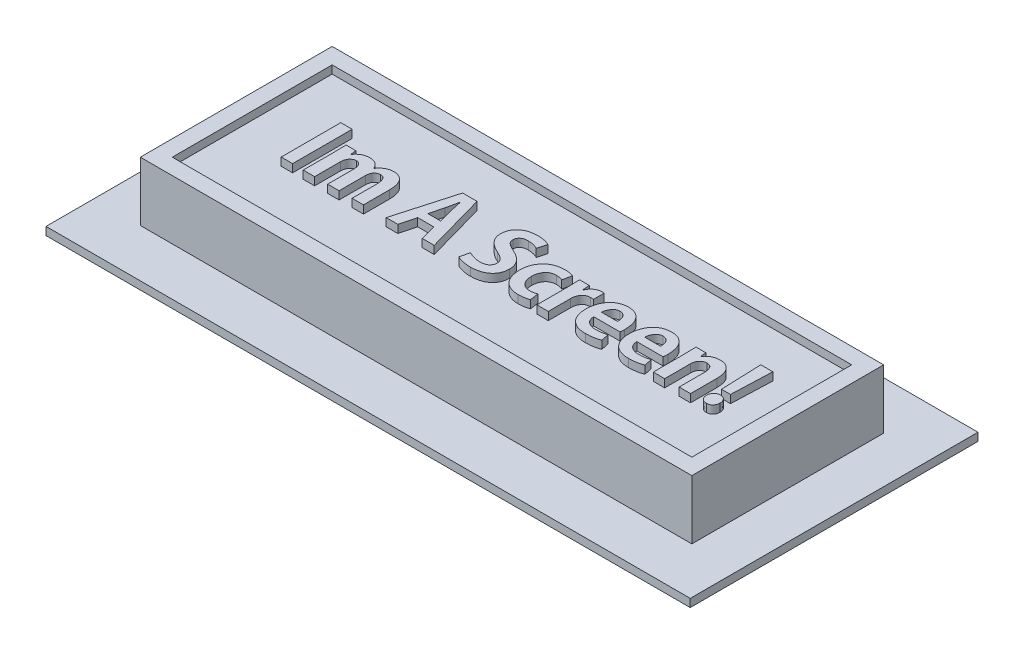
SolidWorks part; units mm, degrees
ref_plane "Front Plane" through (0, 0, 0) normal (0, 0, 1) x (1, 0, 0)
ref_plane "Top Plane" through (0, 0, 0) normal (0, 1, 0) x (1, 0, 0)
ref_plane "Right Plane" through (0, 0, 0) normal (1, 0, 0) x (0, 0, -1)
sketch "Sketch1" plane through (0, 0, 0) normal (0, 1, 0) x (1, 0, 0)
  line L1 (40.3, -18) -> (-40.3, -18)
  line L2 (40.3, -18) -> (40.3, 18)
  line L3 (40.3, 18) -> (-40.3, 18)
  line L4 (-40.3, -18) -> (-40.3, 18)
  line L5 (40.3, -18) -> (-40.3, 18) construction
  line L6 (40.3, 18) -> (-40.3, -18) construction
  point P0 (0, 0)
  dimension "D1" = 36
  dimension "D2" = 80.6
extrude "Boss-Extrude1" add sketch "Sketch1" against normal blind 1
sketch "Sketch2" plane through (0, 0, 0) normal (0, 1, 0) x (1, 0, 0)
  line L1 (34.5, -12) -> (-34.5, -12)
  line L2 (34.5, -12) -> (34.5, 12)
  line L3 (34.5, 12) -> (-34.5, 12)
  line L4 (-34.5, -12) -> (-34.5, 12)
  line L5 (34.5, -12) -> (-34.5, 12) construction
  line L6 (34.5, 12) -> (-34.5, -12) construction
  point P0 (0, 0)
  dimension "D1" = 24
  dimension "D2" = 69
extrude "Boss-Extrude2" add sketch "Sketch2" along normal blind 7.4
sketch "Sketch3" plane through (0, 7.4, 0) normal (0, 1, 0) x (1, 0, 0)
  line L16 (32.5, -10) -> (32.5, 10)
  line L17 (-32.5, -10) -> (32.5, -10)
  line L18 (-32.5, 10) -> (-32.5, -10)
  line L19 (32.5, 10) -> (-32.5, 10)
  line L20 (32.5, -10) -> (32.5, 10)
  line L21 (-32.5, -10) -> (32.5, -10)
  line L22 (-32.5, 10) -> (-32.5, -10)
  line L23 (32.5, 10) -> (-32.5, 10)
  dimension "D1" = 2
extrude "Cut-Extrude1" cut sketch "Sketch3" against normal blind 1
sketch "Sketch4" plane through (0, 6.4, 0) normal (0, 1, 0) x (1, 0, 0)
  text T0 "Im A Screen!" font "@Adobe Gothic Std B" height in points 24
extrude "Boss-Extrude3" add sketch "Sketch4" along normal blind 1
